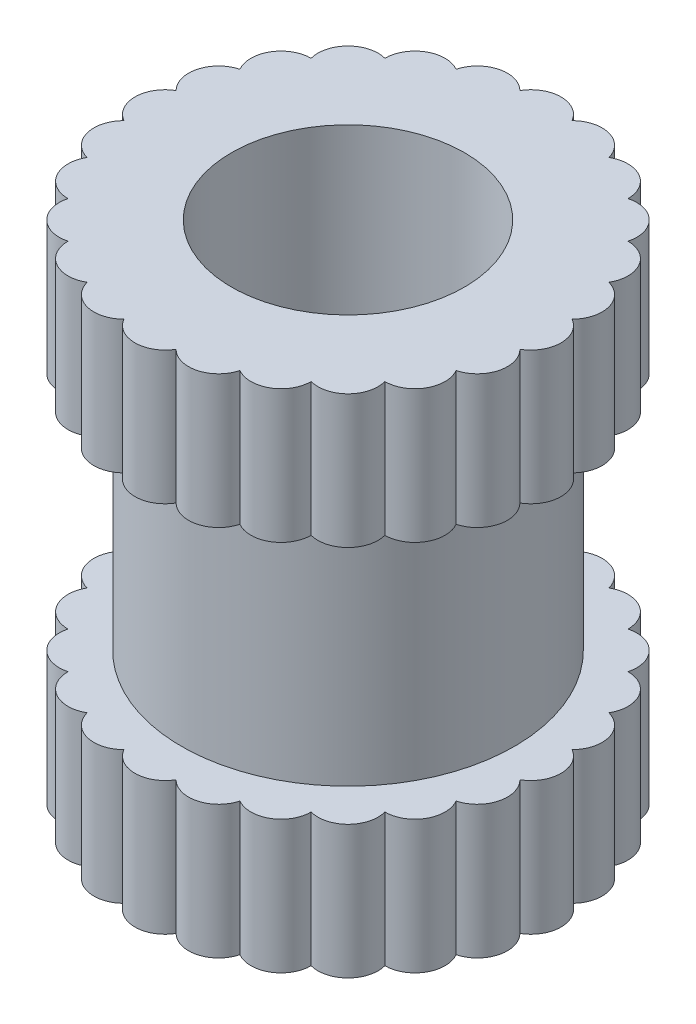
SolidWorks part; units mm, degrees
ref_plane "Front Plane" through (0, 0, 0) normal (0, 0, 1) x (1, 0, 0)
ref_plane "Top Plane" through (0, 0, 0) normal (0, 1, 0) x (1, 0, 0)
ref_plane "Right Plane" through (0, 0, 0) normal (1, 0, 0) x (0, 0, -1)
sketch "Sketch1" plane through (0, 0, 0) normal (0, 1, 0) x (1, 0, 0)
  circle A0 centre (0, 0) radius 1.6
  circle A1 centre (0, 0) radius 0.875
  dimension "D1" = 3.2
  dimension "D2" = 1.75
extrude "Boss-Extrude1" add sketch "Sketch1" along normal blind 3.8
sketch "Sketch2" plane through (0, 0, 0) normal (1, 0, 0) x (0, 0, -1)
  line L0 (1.6, 0) -> (1.6, 3.8) construction
  line L1 (1.25, 2.8) -> (1.6, 2.8)
  line L2 (1.25, 2.8) -> (1.25, 1)
  line L3 (1.25, 1) -> (1.6, 1)
  line L4 (1.6, 2.8) -> (1.6, 1)
  line L5 (1.6, 3.8) -> (-1.6, 3.8) construction
  line L6 (-1.6, 0) -> (1.6, 0) construction
  line L7 (0, 0) -> (0, 3.8) construction
  dimension "D1" = 1
  dimension "D2" = 1
  dimension "D3" = 2.5
revolve "Cut-Revolve1" cut sketch "Sketch2" angle 360 about L7
sketch "Sketch3" plane through (0, 3.8, 0) normal (0, 1, 0) x (1, 0, 0)
  line L0 (0, 0) -> (0, 2.306) construction
  line L1 (0, 0) -> (0.6023, 2.248) construction
  line L2 (0.1958, 1.4872) -> (0, 0) construction
  arc A0 (0, 1.6) -> (0.1958, 1.4872) centre (0, 1.3737) cw
  arc A1 (0.1958, 1.4872) -> (0.4141, 1.5455) centre (0.3555, 1.3269) cw
  circle A2 centre (0, 0) radius 1.6 construction
  arc A3 (0.4141, 1.5455) -> (0, 1.6) centre (0, 0) ccw
  dimension "D1" = 15
  dimension "D2" = 7.5
  dimension "D3" = 1.5
extrude "Cut-Extrude1" cut sketch "Sketch3" against normal through all
pattern_circular "CirPattern1" count 24 over 360 about axis through (0, 0, 0) along (0, 1, 0) of "Cut-Extrude1"
